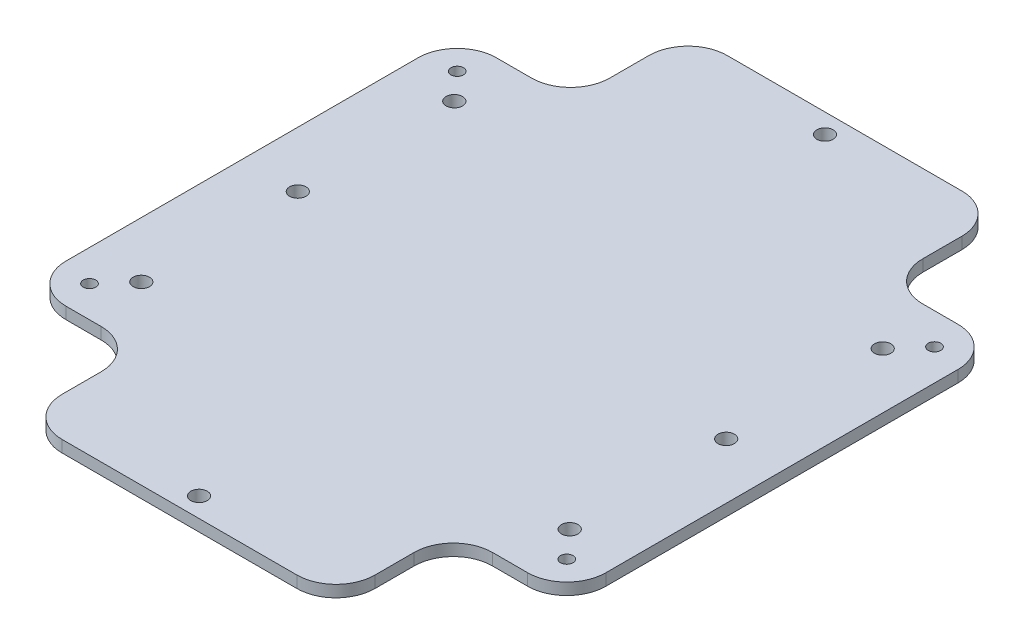
SolidWorks part; units mm, degrees
ref_plane "Front Plane" through (0, 0, 0) normal (0, 0, 1) x (1, 0, 0)
ref_plane "Top Plane" through (0, 0, 0) normal (0, 1, 0) x (1, 0, 0)
ref_plane "Right Plane" through (0, 0, 0) normal (1, 0, 0) x (0, 0, -1)
sketch "Sketch1" plane through (0, 0, 0) normal (0, 1, 0) x (1, 0, 0)
  line L1 (0, 0) -> (138, 0)
  line L2 (0, 0) -> (0, 170)
  line L3 (0, 170) -> (138, 170)
  line L4 (138, 0) -> (138, 170)
  dimension "D1" = 138
  dimension "D2" = 170
extrude "Boss-Extrude1" add sketch "Sketch1" along normal blind 3
sketch "Sketch2" plane through (0, 3, 0) normal (0, 1, 0) x (1, 0, 0)
  line L0 (0, 132) -> (138, 132) construction
  line L1 (0, 170) -> (29, 170)
  line L2 (0, 170) -> (0, 140)
  line L3 (0, 140) -> (29, 140)
  line L4 (29, 170) -> (29, 140)
  line L5 (138, 170) -> (109, 170)
  line L6 (138, 170) -> (138, 140)
  line L7 (138, 140) -> (109, 140)
  line L8 (109, 170) -> (109, 140)
  line L9 (138, 0) -> (109, 0)
  line L10 (138, 0) -> (138, 30)
  line L11 (138, 30) -> (109, 30)
  line L12 (109, 0) -> (109, 30)
  line L13 (0, 0) -> (29, 0)
  line L14 (0, 0) -> (0, 30)
  line L15 (0, 30) -> (29, 30)
  line L16 (29, 0) -> (29, 30)
  line L18 (0, 38) -> (138, 38) construction
  line L20 (29, 165) -> (109, 165) construction
  line L21 (29, 5) -> (109, 5) construction
  line L22 (69, 165) -> (69, 5) construction
  line L23 (138, 0) -> (138, 170) construction
  line L24 (69, 85) -> (138, 85) construction
  line L25 (0, 170) -> (0, 0) construction
  line L26 (10, 160) -> (10, 10)
  line L27 (10, 10) -> (128, 10)
  line L28 (128, 10) -> (128, 160)
  line L29 (128, 160) -> (10, 160)
  line L30 (10, 160) -> (10, 10) construction
  line L31 (10, 10) -> (128, 10) construction
  line L32 (128, 10) -> (128, 160) construction
  line L33 (128, 160) -> (10, 160) construction
  line L34 (138, 170) -> (0, 170) construction
  circle A220 centre (69, 165) radius 2.1
  circle A221 centre (69, 5) radius 2.1
  point P225 (69, 170)
  dimension "D12" = 4.2
  dimension "D13" = 4.2
  dimension "D1" = 30
  dimension "D2" = 160
  dimension "D5" = 8
  dimension "D9" = 30
  dimension "D10" = 80
  dimension "D11" = 8
  dimension "D3" = 10
extrude "Cut-Extrude1" cut sketch "Sketch2" against normal blind 3
sketch "Sketch3" plane through (0, 3, 0) normal (0, 1, 0) x (1, 0, 0)
  line L0 (69, 170) -> (69, 139.75) construction
  line L1 (14.25, 139.75) -> (123.75, 139.75) construction
  line L2 (14.25, 139.75) -> (14.25, 30.25) construction
  line L3 (14.25, 30.25) -> (123.75, 30.25) construction
  line L4 (123.75, 139.75) -> (123.75, 30.25) construction
  line L5 (109, 170) -> (29, 170) construction
  line L7 (14.25, 85) -> (0, 85) construction
  line L8 (0, 140) -> (0, 30) construction
  line L9 (8, 140) -> (8, 30) construction
  line L10 (0, 140) -> (29, 140) construction
  line L11 (29, 30) -> (0, 30) construction
  line L13 (130, 140) -> (130, 30) construction
  line L14 (109, 140) -> (138, 140) construction
  line L15 (138, 30) -> (109, 30) construction
  circle A0 centre (14.25, 125) radius 2.1
  circle A1 centre (14.25, 45) radius 2.1
  circle A2 centre (14.25, 85) radius 2.1
  circle A3 centre (123.75, 45) radius 2.1
  circle A4 centre (123.75, 85) radius 2.1
  circle A5 centre (123.75, 125) radius 2.1
  circle A57 centre (8, 132) radius 1.6
  circle A58 centre (8, 38) radius 1.6
  circle A59 centre (130, 38) radius 1.6
  circle A60 centre (130, 132) radius 1.6
  point P23 (0, 0)
  point P26 (14.25, 107.5)
  point P31 (5, 132.1319)
  point P32 (5, 37.0797)
  point P34 (6.6971, 109.215)
  point P41 (0, 0)
  point P42 (123.75, 30.25)
  point P43 (6.6946, 60.7581)
  dimension "D3" = 4.2
  dimension "D4" = 40
  dimension "D6" = 8
  dimension "D7" = 3.2
  dimension "D8" = 8
  dimension "D1" = 109.5
  dimension "D2" = 109.5
  dimension "D5" = 40
  dimension "D9" = 8
extrude "Cut-Extrude2" cut sketch "Sketch3" against normal through all
fillet "Fillet1" radius 10 12 edges at (29, 1.5, -170) (29, 1.5, -140) (0, 1.5, -140) (0, 1.5, -30) (29, 1.5, -30) (29, 1.5, 0) (109, 1.5, 0) (109, 1.5, -30) (138, 1.5, -30) (109, 1.5, -140) (138, 1.5, -140) (109, 1.5, -170)
